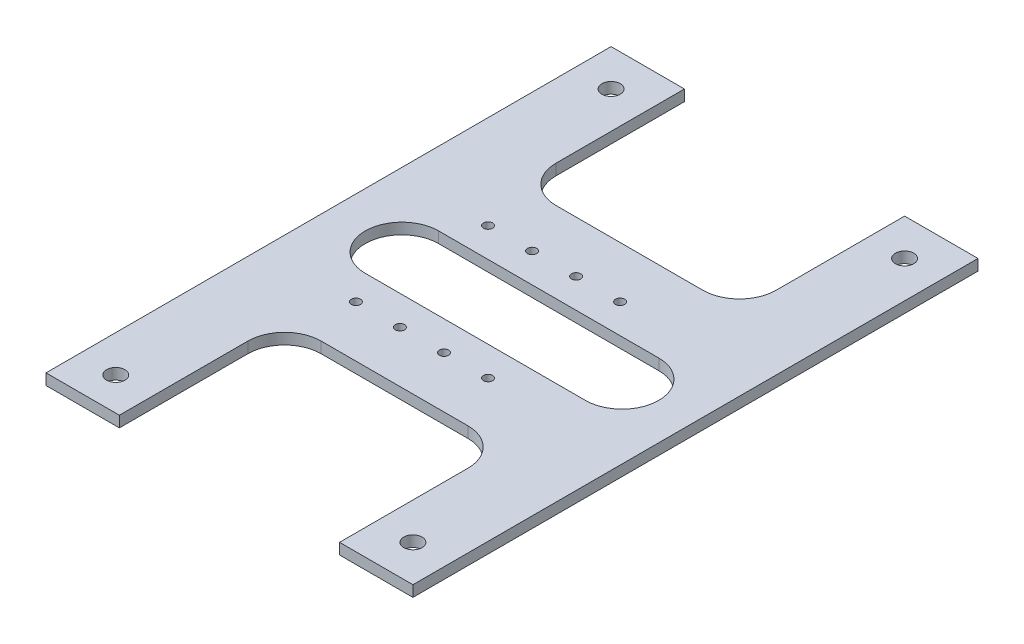
SolidWorks part; units mm, degrees
ref_plane "정면" through (0, 0, 0) normal (0, 0, 1) x (1, 0, 0)
ref_plane "윗면" through (0, 0, 0) normal (0, 1, 0) x (1, 0, 0)
ref_plane "우측면" through (0, 0, 0) normal (1, 0, 0) x (0, 0, -1)
sketch "스케치1" plane through (0, -15.6919, 0) normal (0, 1, 0) x (1, 0, 0)
  line L0 (1020.801, -128.9738) -> (960.801, -128.9738) construction
  line L1 (944.328, -78.9738) -> (1044.328, -78.9738)
  line L2 (944.328, -78.9738) -> (944.328, -232.9738)
  line L3 (944.328, -232.9738) -> (1044.328, -232.9738)
  line L4 (1044.328, -78.9738) -> (1044.328, -232.9738)
  line L5 (960.801, -182.9738) -> (1020.801, -182.9738) construction
  line L6 (1044.328, -330.9738) -> (1044.328, 19.0262) construction
  circle A0 centre (1034.328, -88.9738) radius 2.5
  circle A1 centre (1034.328, -222.9738) radius 2.5
  circle A2 centre (954.328, -223.9565) radius 2.5
  circle A3 centre (954.328, -88.9738) radius 2.5
  dimension "D4" = 10
  dimension "D5" = 5
  dimension "D8" = 10
  dimension "D9" = 5
  dimension "D10" = 5
  dimension "D11" = 5
  dimension "D1" = 50
  dimension "D2" = 50
  dimension "D3" = 100
  dimension "D6" = 10
  dimension "D7" = 10
  dimension "D12" = 10
  dimension "D13" = 10
  dimension "D14" = 10
extrude "보스-돌출1" add sketch "스케치1" along normal blind 3
sketch "스케치4" plane through (0, -12.6919, 0) normal (0, 1, 0) x (1, 0, 0)
  circle A0 centre (969.801, -137.9738) radius 1.25
  circle A1 centre (1005.801, -137.9738) radius 1.25
  circle A2 centre (1005.801, -173.9738) radius 1.25
  circle A3 centre (969.801, -173.9738) radius 1.25
  circle A4 centre (993.801, -137.9738) radius 1.25
  circle A5 centre (981.801, -137.9738) radius 1.25
  circle A6 centre (981.801, -173.9738) radius 1.25
  circle A7 centre (993.801, -173.9738) radius 1.25
extrude "컷-돌출1" cut sketch "스케치4" against normal blind 3
sketch "스케치5" plane through (0, -12.6919, 0) normal (0, 1, 0) x (1, 0, 0)
  line L6 (964.328, -78.8756) -> (1024.328, -78.8756)
  line L11 (964.328, -78.8756) -> (964.328, -113.9738)
  line L12 (974.328, -123.9738) -> (1014.328, -123.9738)
  line L13 (1024.328, -78.8756) -> (1024.328, -113.9738)
  line L14 (964.328, -238.3989) -> (1024.328, -238.3989)
  line L15 (964.328, -238.3989) -> (964.328, -197.9738)
  line L16 (974.328, -187.9738) -> (1014.328, -187.9738)
  line L17 (1024.328, -238.3989) -> (1024.328, -197.9738)
  line L22 (1044.328, -78.9738) -> (944.328, -78.9738) construction
  line L23 (944.328, -232.9738) -> (1044.328, -232.9738) construction
  line L24 (944.328, -78.9738) -> (944.328, -232.9738) construction
  line L25 (1044.328, -232.9738) -> (1044.328, -78.9738) construction
  arc A0 (1014.328, -187.9738) -> (1024.328, -197.9738) centre (1014.328, -197.9738) cw
  arc A1 (964.328, -197.9738) -> (974.328, -187.9738) centre (974.328, -197.9738) cw
  arc A2 (1014.328, -123.9738) -> (1024.328, -113.9738) centre (1014.328, -113.9738) ccw
  arc A3 (964.328, -113.9738) -> (974.328, -123.9738) centre (974.328, -113.9738) ccw
  dimension "D7" = 10
  dimension "D1" = 45
  dimension "D2" = 20
  dimension "D3" = 45
  dimension "D4" = 20
  dimension "D5" = 20
  dimension "D6" = 20
extrude "컷-돌출2" cut sketch "스케치5" against normal blind 10
sketch "스케치6" plane through (0, -12.6919, 0) normal (0, 1, 0) x (1, 0, 0)
  line L0 (964.328, -155.9738) -> (1024.328, -155.9738) construction
  line L1 (964.328, -145.9738) -> (1024.328, -145.9738)
  line L2 (964.328, -165.9738) -> (1024.328, -165.9738)
  line L3 (944.328, -78.9738) -> (944.328, -232.9738) construction
  line L4 (1044.328, -232.9738) -> (1044.328, -78.9738) construction
  arc A0 (964.328, -145.9738) -> (964.328, -165.9738) centre (964.328, -155.9738) ccw
  arc A1 (1024.328, -165.9738) -> (1024.328, -145.9738) centre (1024.328, -155.9738) ccw
  point P2 (994.328, -155.9738)
  dimension "D3" = 10
  dimension "D1" = 20
  dimension "D2" = 20
extrude "컷-돌출3" cut sketch "스케치6" against normal blind 10
